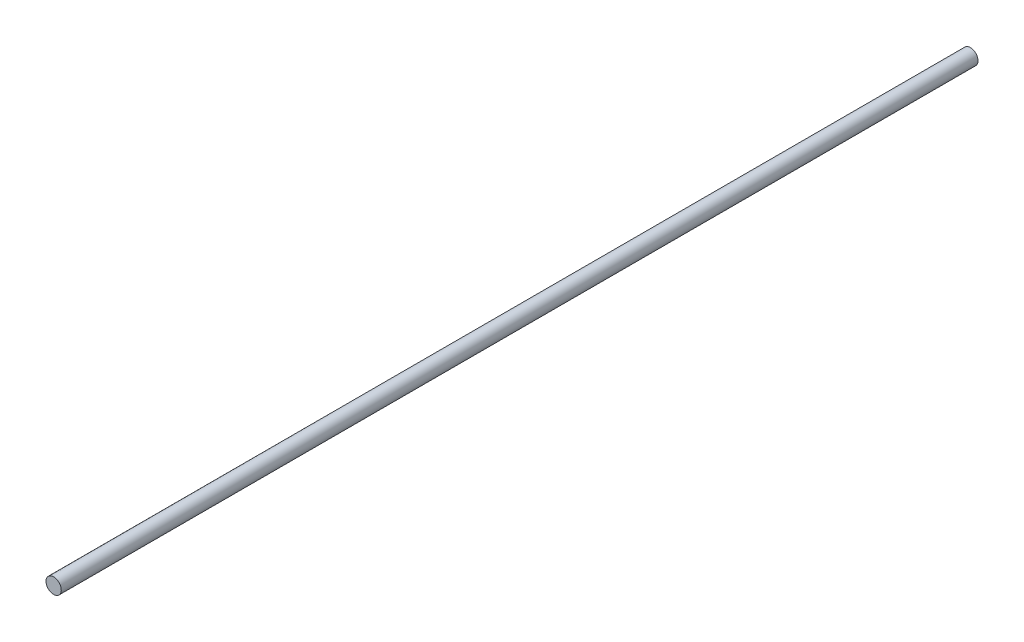
SolidWorks part; units mm, degrees
material "Plain Carbon Steel"
ref_plane "Front Plane" through (0, 0, 0) normal (0, 0, 1) x (1, 0, 0)
ref_plane "Top Plane" through (0, 0, 0) normal (0, 1, 0) x (1, 0, 0)
ref_plane "Right Plane" through (0, 0, 0) normal (1, 0, 0) x (0, 0, -1)
sketch "Sketch1" plane through (0, 0, 0) normal (0, 0, 1) x (1, 0, 0)
  circle A0 centre (0, 0) radius 5
  dimension "D1" = 10
extrude "Boss-Extrude1" add sketch "Sketch1" along normal blind 600
